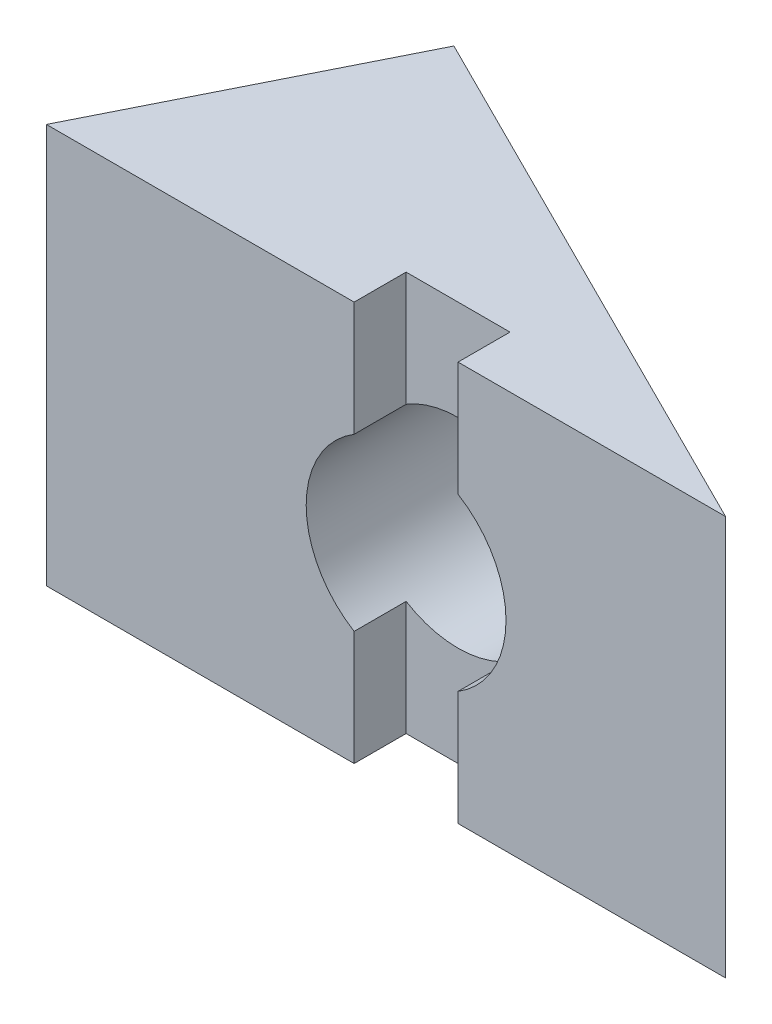
SolidWorks part; units mm, degrees
ref_plane "Piano frontale" through (0, 0, 0) normal (0, 0, 1) x (1, 0, 0)
ref_plane "Piano superiore" through (0, 0, 0) normal (0, 1, 0) x (1, 0, 0)
ref_plane "Piano destro" through (0, 0, 0) normal (1, 0, 0) x (0, 0, -1)
sketch "Schizzo1" plane through (0, 0, 0) normal (0, 1, 0) x (1, 0, 0)
  line L0 (-52.4969, -55.3916) -> (117.4443, -55.3916)
  line L1 (117.4443, -55.3916) -> (-18.5086, 12.5849)
  line L2 (-18.5086, 12.5849) -> (-52.4969, -55.3916)
  dimension "D1" = 90
  dimension "D2" = 152
  dimension "D3" = 76
extrude "Estrusione-Estrusione1" add sketch "Schizzo1" along normal blind 100
sketch "Schizzo2" plane through (0, 0, 55.3916) normal (0, 0, 1) x (1, 0, 0)
  line L0 (37.5031, 100) -> (37.5031, 0) construction
  line L1 (-52.4969, 100) -> (117.4443, 100) construction
  line L2 (-52.4969, 0) -> (117.4443, 0) construction
  line L3 (50.5031, 100) -> (24.5031, 100)
  line L4 (24.5031, 100) -> (24.5031, 0)
  line L5 (24.5031, 0) -> (50.5031, 0)
  line L6 (50.5031, 100) -> (50.5031, 0)
  circle A0 centre (37.5031, 50) radius 25
  line M2 (-52.4969, 0) -> (117.4443, 0)
  line M4 (117.4443, 100) -> (-52.4969, 100)
  dimension "D2" = 50
  dimension "D1" = 90
  dimension "D3" = 50
  dimension "D4" = 26
extrude "Taglio-Estrusione2" cut sketch "Schizzo2" against normal blind 13 contours L0 A0 L6 M4 | L0 L3 L4 A0 | A0 L0 L5 L6 | L0 A0 L4 M2
sketch "Schizzo5" plane through (0, 0, 55.3916) normal (0, 0, 1) x (1, 0, 0)
  line L0 (37.5031, 25) -> (37.5031, 75) construction
  arc A0 (24.5031, 28.6458) -> (50.5031, 28.6458) centre (37.5031, 50) ccw construction
  arc A1 (50.5031, 71.3542) -> (24.5031, 71.3542) centre (37.5031, 50) ccw construction
  circle A2 centre (37.5031, 50) radius 25
extrude "Taglio-Estrusione3" cut sketch "Schizzo5" against normal through all
